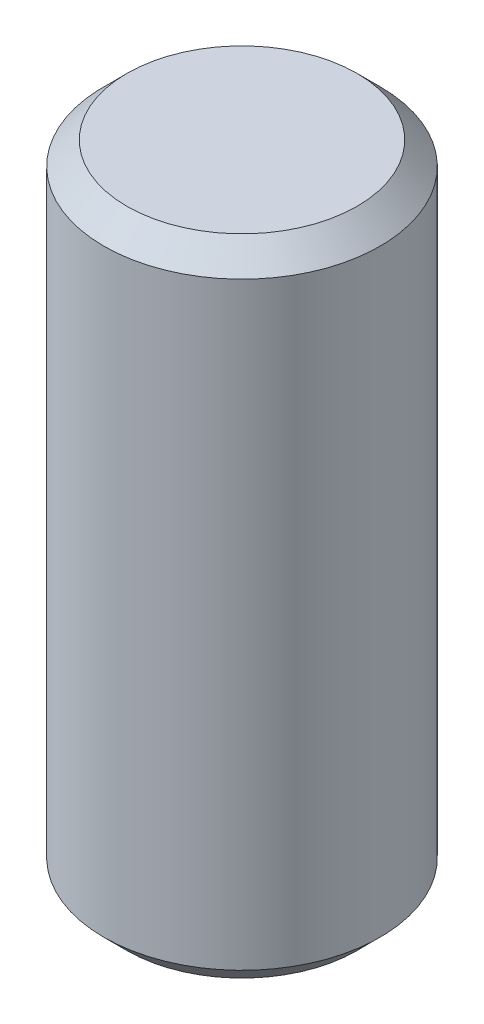
SolidWorks part; units mm, degrees
ref_plane "Front" through (0, 0, 0) normal (0, 0, 1) x (1, 0, 0)
ref_plane "Top" through (0, 0, 0) normal (0, 1, 0) x (1, 0, 0)
ref_plane "Right" through (0, 0, 0) normal (1, 0, 0) x (0, 0, -1)
sketch "Sketch24" plane through (0, 0, 0) normal (1, 0, 0) x (0, 0, -1)
  line L5 (0, 3.825) -> (0, -3.825) construction
  line L6 (-1, -3.3398) -> (-1, -2.5083) construction
  line L7 (-1.25, -3.175) -> (-1.25, 3.825) construction
  line L8 (-1.25, -3.175) -> (-1.5, -2.925)
  line L9 (-1.25, -3.175) -> (-1.5, -3.175) construction
  line L10 (-1.5, -2.925) -> (-1.5, 3.575)
  line L11 (-1.5, 3.575) -> (-1.25, 3.825)
  line L12 (-1.25, 3.825) -> (0, 3.825)
  line L13 (0, -3.825) -> (0, 3.825) construction
  line L16 (-1.25, -3.175) -> (-1, -3.175)
  line L17 (-1.3476, -2.5083) -> (0, -2.5083) construction
  line L18 (0, -2.5083) -> (0, 3.825)
  line L19 (-1, -3.175) -> (-1, -2.5083)
  line L20 (-1, -2.5083) -> (0, -2.5083)
  circle A1 centre (0, -2.825) radius 1 construction
  dimension "D1" = 7
  dimension "Ball Dia" = 2
  dimension "D4" = 45
  dimension "D2" = 45
  dimension "Body Dia" = 3
  dimension "D3" = 0.6667
  dimension "Ball Projection" = 0.65
revolve "Revolve2" add sketch "Sketch24" angle 360 about L5
sketch "Sketch25" plane through (0, 0, 0) normal (1, 0, 0) x (0, 0, -1)
  line L0 (0, -3.825) -> (0, -1.825)
  circle A0 centre (0, -2.825) radius 1 construction
  arc A2 (0, -3.825) -> (0, -1.825) centre (0, -2.825) cw
revolve "Revolve3" add sketch "Sketch25" angle 360 about L18
equation "\"D3@Sketch24\" = \"Ball Dia@Sketch24\"/3"
